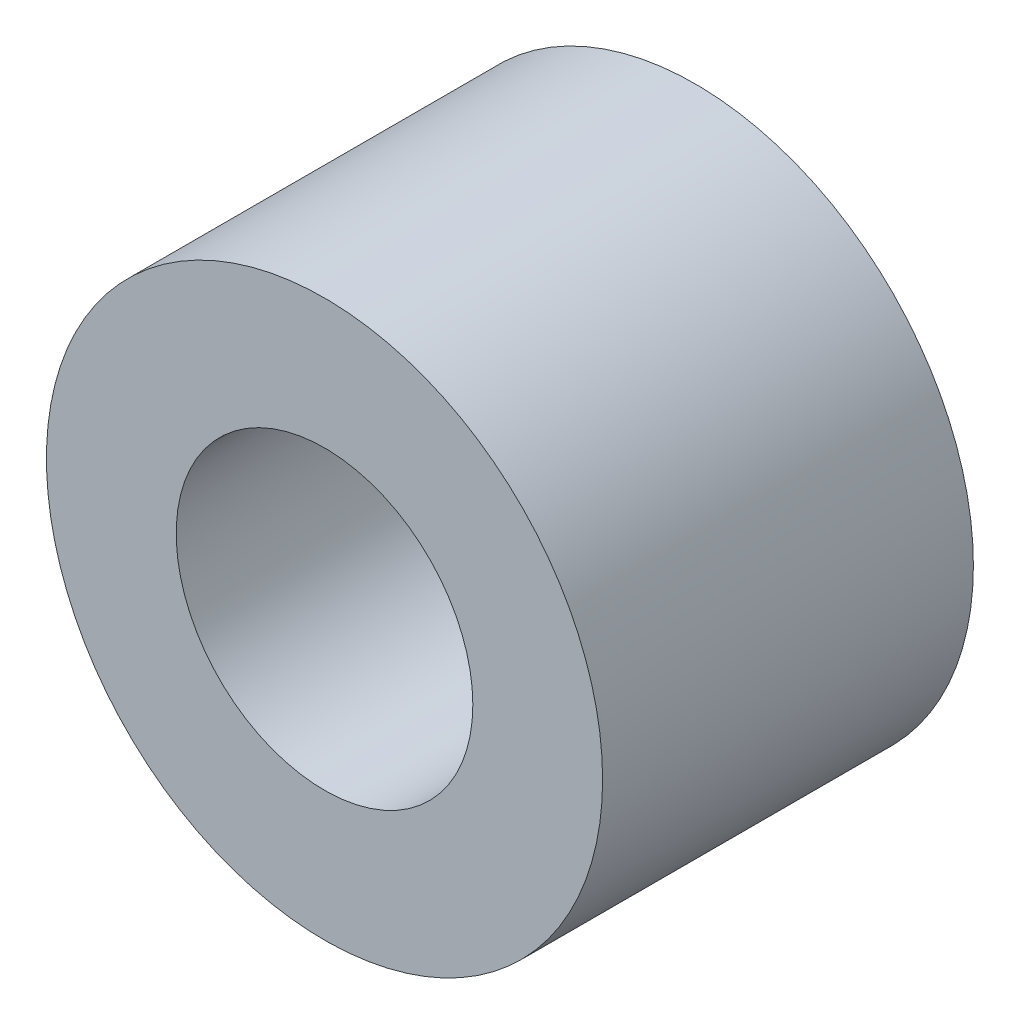
SolidWorks part; units mm, degrees
material "ABS"
ref_plane "前视基准面" through (0, 0, 0) normal (0, 0, 1) x (1, 0, 0)
ref_plane "上视基准面" through (0, 0, 0) normal (0, 1, 0) x (1, 0, 0)
ref_plane "右视基准面" through (0, 0, 0) normal (1, 0, 0) x (0, 0, -1)
sketch "草图1" plane through (0, 0, 0) normal (0, 0, 1) x (1, 0, 0)
  circle A0 centre (0, 0) radius 3
  circle A1 centre (0, 0) radius 1.6
  dimension "D1" = 3.2
  dimension "D2" = 6
extrude "凸台-拉伸1" add sketch "草图1" along normal blind 4
